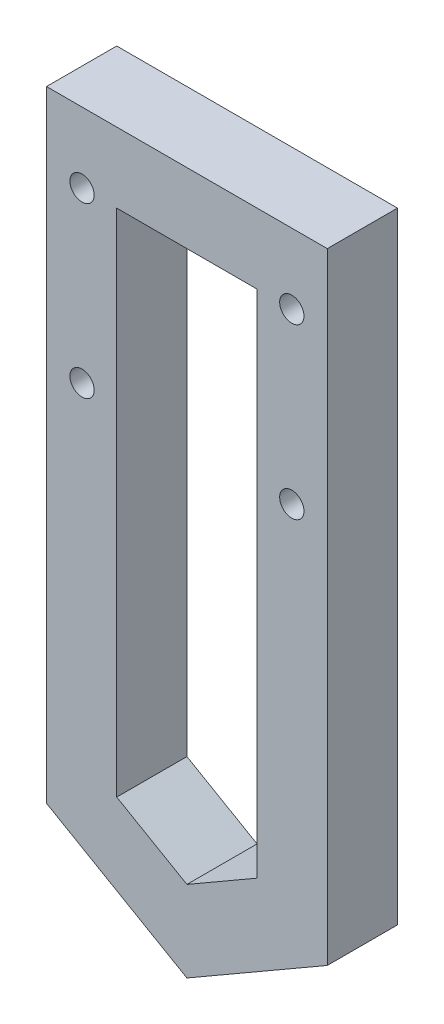
SolidWorks part; units mm, degrees
ref_plane "Front Plane" through (0, 0, 0) normal (0, 0, 1) x (1, 0, 0)
ref_plane "Top Plane" through (0, 0, 0) normal (0, 1, 0) x (1, 0, 0)
ref_plane "Right Plane" through (0, 0, 0) normal (1, 0, 0) x (0, 0, -1)
sketch "Sketch1" plane through (0, 0, 0) normal (0, 0, 1) x (1, 0, 0)
  line L0 (-32.7974, 238.3187) -> (-32.7974, 38.3187)
  line L1 (-132.7974, 238.3187) -> (67.2026, 238.3187)
  line L2 (-132.7974, 238.3187) -> (-132.7974, 38.3187)
  line L3 (-132.7974, 38.3187) -> (67.2026, 38.3187)
  line L4 (67.2026, 238.3187) -> (67.2026, 38.3187)
  line L5 (-132.7974, 138.3187) -> (-32.7974, 138.3187)
  line L6 (-32.7974, 138.3187) -> (67.2026, 138.3187)
  line L7 (-32.7974, 138.3187) -> (53.8052, 88.3187)
  line L8 (-32.7974, 138.3187) -> (-119.3999, 88.3187)
  line L9 (53.8052, 88.3187) -> (43.8052, 70.9982)
  line L10 (53.8052, 88.3187) -> (63.8052, 105.6392)
  line L11 (43.8052, 70.9982) -> (-32.7974, 115.2247)
  line L12 (63.8052, 105.6392) -> (-12.7974, 149.8657)
  line L13 (-12.7974, 149.8657) -> (-32.7974, 138.3187)
  line L14 (-32.7974, 115.2247) -> (-32.7974, 138.3187)
  line L15 (63.8052, 105.6392) -> (55.1449, 110.6392)
  line L16 (55.1449, 110.6392) -> (35.1449, 75.9982)
  line L17 (43.8052, 70.9982) -> (48.8052, 79.6585)
  line L18 (48.8052, 79.6585) -> (-32.7974, 126.7717)
  line L19 (63.8052, 105.6392) -> (58.8052, 96.979)
  line L20 (58.8052, 96.979) -> (-22.7974, 144.0922)
  line L21 (-42.7974, 126.7717) -> (-22.7974, 126.7717)
  line L22 (-22.7974, 144.0922) -> (-17.7974, 135.432)
  line L23 (-17.7974, 135.432) -> (-12.7974, 138.3187)
  line L24 (-22.7974, 126.7717) -> (-22.7974, 120.9982)
  line L25 (-22.7974, 126.7717) -> (-22.7974, 132.5452)
  line L26 (-17.7974, 135.432) -> (-22.7974, 132.5452)
  line L27 (-109.3999, 70.9982) -> (-32.7974, 115.2247)
  line L28 (-32.7974, 138.3187) -> (-119.3999, 88.3187)
  line L29 (-114.3999, 79.6585) -> (-32.7974, 126.7717)
  line L30 (-119.3999, 88.3187) -> (-109.3999, 70.9982)
  line L31 (-119.3999, 88.3187) -> (-129.3999, 105.6392)
  line L32 (-120.7397, 110.6392) -> (-100.7397, 75.9982)
  line L33 (-129.3999, 105.6392) -> (-52.7974, 149.8657)
  line L34 (-124.3999, 96.979) -> (-42.7974, 144.0922)
  line L35 (-52.7974, 149.8657) -> (-32.7974, 138.3187)
  line L36 (-47.7974, 135.432) -> (-42.7974, 132.5452)
  line L37 (-42.7974, 126.7717) -> (-42.7974, 132.5452)
  line L38 (-42.7974, 126.7717) -> (-42.7974, 120.9982)
  line L39 (-47.7974, 135.432) -> (-52.7974, 138.3187)
  line L40 (-42.7974, 144.0922) -> (-47.7974, 135.432)
  line L41 (-52.7974, 149.8657) -> (-52.7974, 238.3187)
  line L42 (-12.7974, 149.8657) -> (-12.7974, 238.3187)
  line L43 (-32.7974, 238.3187) -> (-32.7974, 228.3187)
  line L44 (-32.7974, 228.3187) -> (-42.7974, 228.3187)
  line L45 (-42.7974, 228.3187) -> (-42.7974, 144.0922)
  line L46 (-22.7974, 144.0922) -> (-22.7974, 228.3187)
  line L47 (-22.7974, 228.3187) -> (-32.7974, 228.3187)
  line L48 (-37.7974, 152.7525) -> (-32.7974, 149.8657)
  line L49 (-37.7974, 152.7525) -> (-42.7974, 155.6392)
  line L50 (-27.7974, 152.7525) -> (-22.7974, 155.6392)
  line L51 (-27.7974, 152.7525) -> (-32.7974, 149.8657)
extrude "Boss-Extrude1" add sketch "Sketch1" along normal blind 10 contours L47 L46 L13 L42 L1 L0 | L45 L44 L0 L1 L41 L35 | L48 L49 L45 L35 L0 | L50 L51 L0 L13 L46
sketch "Sketch3" plane through (0, 0, 10) normal (0, 0, 1) x (1, 0, 0)
  line L0 (-52.7974, 238.3187) -> (-47.7424, 238.3187)
  line L1 (-52.7974, 238.3187) -> (-12.7974, 238.3187) construction
  line L2 (-47.7424, 238.3187) -> (-47.7424, 228.3187)
  line L3 (-47.7424, 228.3187) -> (-17.8524, 228.3187)
  line L4 (-17.8524, 228.3187) -> (-17.8524, 238.3187)
  line L5 (-17.8524, 238.3187) -> (-12.7974, 238.3187)
  line L6 (-47.7424, 228.3187) -> (-47.7424, 204.2587)
  line L7 (-32.7974, 228.3187) -> (-32.7974, 196.6)
  circle A0 centre (-47.7424, 228.3187) radius 1.73
  circle A1 centre (-47.7424, 204.2587) radius 1.73
  circle A2 centre (-17.8524, 204.2587) radius 1.73
  circle A3 centre (-17.8524, 228.3187) radius 1.73
extrude "Cut-Extrude1" cut sketch "Sketch3" against normal blind 10
